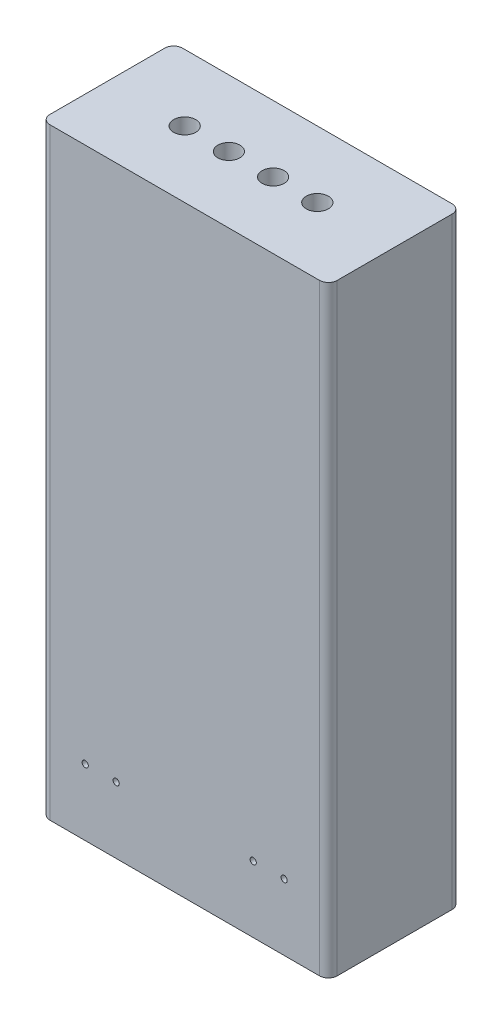
SolidWorks part; units mm, degrees
material "Mahogany"
ref_plane "Front Plane" through (0, 0, 0) normal (0, 0, 1) x (1, 0, 0)
ref_plane "Top Plane" through (0, 0, 0) normal (0, 1, 0) x (1, 0, 0)
ref_plane "Right Plane" through (0, 0, 0) normal (1, 0, 0) x (0, 0, -1)
sketch "Sketch1" plane through (0, 0, 0) normal (0, 0, 1) x (1, 0, 0)
  line L1 (-41.275, -86.5188) -> (41.275, -86.5188)
  line L2 (-41.275, -86.5188) -> (-41.275, 86.5187)
  line L3 (-41.275, 86.5187) -> (41.275, 86.5187)
  line L4 (41.275, -86.5188) -> (41.275, 86.5187)
  line L5 (-41.275, -86.5188) -> (41.275, 86.5187) construction
  line L6 (-41.275, 86.5187) -> (41.275, -86.5188) construction
  point P0 (0, 0)
  dimension "D1" = 173.0375
  dimension "D2" = 82.55
extrude "Boss-Extrude1" add sketch "Sketch1" along normal mid plane 38.1
sketch "Sketch2" plane through (0, 0, 19.05) normal (0, 0, 1) x (1, 0, 0)
  line L0 (41.275, -86.5188) -> (41.275, 86.5187) construction
  line L1 (-28.575, 67.4688) -> (28.575, 67.4688) construction
  line L2 (-28.575, 67.4688) -> (-28.575, -67.4688) construction
  line L3 (-28.575, -67.4688) -> (28.575, -67.4688) construction
  line L4 (28.575, 67.4688) -> (28.575, -67.4688) construction
  line L5 (-28.575, 67.4688) -> (28.575, -67.4688) construction
  line L6 (-28.575, -67.4688) -> (28.575, 67.4688) construction
  line L7 (-41.275, -86.5188) -> (41.275, -86.5188) construction
  circle A0 centre (-28.575, -67.4688) radius 0.889
  circle A1 centre (-19.685, -67.4688) radius 0.889
  circle A2 centre (28.575, -67.4688) radius 0.889
  circle A3 centre (19.685, -67.4688) radius 0.889
  point P0 (0, 0)
  dimension "D3" = 1.778
  dimension "D1" = 12.7
  dimension "D2" = 19.05
  dimension "D4" = 8.89
  dimension "D5" = 8.89
extrude "Cut-Extrude1" cut sketch "Sketch2" against normal through all
fillet "Fillet1" radius 2.54 4 edges at (41.275, 0, -19.05) (41.275, 0, 19.05) (-41.275, 0, -19.05) (-41.275, 0, 19.05)
sketch "Sketch3" plane through (0, 86.5187, 0) normal (0, 1, 0) x (1, 0, 0)
  line L0 (-6.35, 0) -> (6.35, 0) construction
  circle A0 centre (19.05, 0) radius 3.175
  circle A1 centre (-19.05, 0) radius 3.175
  circle A2 centre (-6.35, 0) radius 3.175
  circle A3 centre (6.35, 0) radius 3.175
  dimension "D1" = 12.7
  dimension "D4" = 6.35
  dimension "D2" = 12.7
  dimension "D3" = 12.7
extrude "Cut-Extrude2" cut sketch "Sketch3" against normal blind 50.8
equation "\"D5@Sketch2\"=\"D4@Sketch2\""
